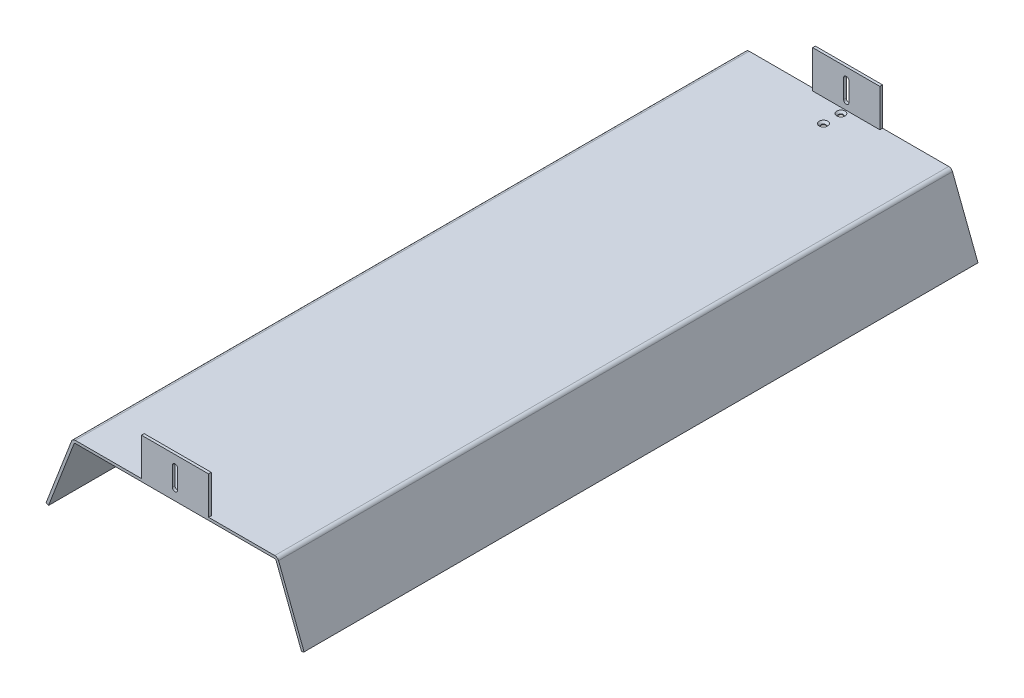
SolidWorks part; units mm, degrees
other "DetailItem1"
other "DetailItem2"
ref_plane "Front Plane" through (0, 0, 0) normal (0, 0, 1) x (1, 0, 0)
ref_plane "Top Plane" through (0, 0, 0) normal (0, 1, 0) x (1, 0, 0)
ref_plane "Right Plane" through (0, 0, 0) normal (1, 0, 0) x (0, 0, -1)
sketch "Sketch1" plane through (0, 0, 0) normal (0, 0, 1) x (1, 0, 0)
  line L0 (0, 113.4211) -> (0, -113.4211) construction
  line L1 (75, 0) -> (-75, 0)
  line L2 (-75, 0) -> (-94.25, -50)
  line L3 (75, 0) -> (94.25, -50)
  point P4 (0, 0)
  point P10 (0, 0)
  dimension "D1" = 150
  dimension "D2" = 188.5
  dimension "D3" = 50
extrude "Extrude-Thin1" add sketch "Sketch1" along normal blind 502 thin contours L1 L2
sketch "Sketch2" plane through (0, 0, 502) normal (0, 0, 1) x (1, 0, 0)
  line L0 (74.3134, 2) -> (-74.3134, 2) construction
  line L1 (-12.5, 2) -> (12.5, 2) construction
  line L2 (-12.5, 2) -> (-12.5, -18) construction
  line L3 (-12.5, -18) -> (12.5, -18) construction
  line L4 (12.5, 2) -> (12.5, -18) construction
  line L5 (0, 2) -> (0, -18) construction
  line L6 (-12.5, -8) -> (12.5, -8) construction
  line L7 (-2.5, -8) -> (2.5, -8) construction
  line L8 (-2.5, -5.5) -> (2.5, -5.5)
  line L9 (-2.5, -10.5) -> (2.5, -10.5)
  arc A0 (-2.5, -5.5) -> (-2.5, -10.5) centre (-2.5, -8) ccw
  arc A1 (2.5, -10.5) -> (2.5, -5.5) centre (2.5, -8) ccw
  point P6 (0, 2)
  point P14 (0, -8)
  dimension "D4" = 10
  dimension "D1" = 20
  dimension "D2" = 25
  dimension "D3" = 5
sketch "Sketch3" plane through (0, 0, 502) normal (0, 0, 1) x (1, 0, 0)
  line L0 (74.3134, 0) -> (-74.3134, 0) construction
  line L1 (-25, 0) -> (25, 0)
  line L2 (-25, 0) -> (-25, 30)
  line L3 (-25, 30) -> (25, 30)
  line L4 (25, 0) -> (25, 30)
  line L5 (0, 22) -> (0, 8) construction
  line L6 (2, 22) -> (2, 8)
  line L7 (-2, 22) -> (-2, 8)
  arc A0 (2, 22) -> (-2, 22) centre (0, 22) ccw
  arc A1 (-2, 8) -> (2, 8) centre (0, 8) ccw
  point P8 (0, 15)
  point P15 (0, 0)
  point P17 (-25, 15)
  dimension "D2" = 14
  dimension "D1" = 4
  dimension "D3" = 50
  dimension "D4" = 30
extrude "Boss-Extrude1" add sketch "Sketch3" against normal blind 2
ref_plane "Plane1" through (0, 0, 251) normal (0, 0, 1) x (1, 0, 0)
mirror "Mirror1" about plane through (0, 0, 251) normal (0, 0, 1) of bodies 102
sketch "Sketch4" plane through (0, 2, 0) normal (0, 1, 0) x (1, 0, 0)
  line L0 (0, -6) -> (0, -19) construction
  line L1 (-25, 0) -> (25, 0) construction
  line L2 (-25, 0) -> (-25, -25) construction
  line L3 (-25, -25) -> (25, -25) construction
  line L4 (25, 0) -> (25, -25) construction
  line L5 (2, -6) -> (2, -19) construction
  line L6 (-2, -6) -> (-2, -19) construction
  line L7 (25, -2) -> (25, 0) construction
  arc A0 (2, -6) -> (-2, -6) centre (0, -6) ccw construction
  arc A1 (-2, -19) -> (2, -19) centre (0, -19) ccw construction
  point P10 (0, -12.5)
  point P16 (-25, -12.5)
  point P18 (0, -6)
  point P20 (0, -19)
  dimension "D3" = 13
  dimension "D1" = 25
  dimension "D2" = 4
hole_wizard "CSK for M3 Countersunk Flat Head Screw1" positions "Sketch4" profile "Sketch5" countersink size "M3" standard "DIN"
sketch "Sketch5" plane through (0, 2, 19) normal (1, 0, 0) x (0, 0, 1)
  line L0 (0, 0) -> (0, 26.0215)
  line L1 (0, 26.0215) -> (1.7, 25)
  line L2 (1.7, 25) -> (1.7, 1.45)
  line L3 (1.7, 1.45) -> (3.15, 0)
  line L5 (3.15, 0) -> (0, 0)
  line L6 (-1.7, 1.45) -> (-3.15, 0) construction
  line L10 (0, 26.0215) -> (-1.7, 25) construction
  line L11 (0, -6.35) -> (0, 107.95) construction
  dimension "Hole Dia." = 3.4
  dimension "Hole Depth" = 25
  dimension "Near C'Sink Dia." = 6.3
  dimension "Near C'Sink Angle" = 90
  dimension "Drill Angle" = 118
mirror "Mirror2" about plane through (0, 0, 251) normal (0, 0, 1) of "CSK for M3 Countersunk Flat Head Screw1"
sketch "Sketch6" plane through (0, 0, 0) normal (0, 0, -1) x (-1, 0, 0)
  line L0 (-96.1165, -49.2814) -> (-77.1131, 0.0779) construction
  line L1 (-88.3081, -29) -> (-68.1156, -29)
  line L3 (-87.9231, -28) -> (-68.1156, -28)
  line L4 (-68.1156, -29) -> (-68.1156, -28)
  line L5 (-88.3081, -29) -> (-87.9231, -28)
  line L6 (12.5, -18) -> (-12.5, -18) construction
  point P2 (-88.1156, -28.5)
  dimension "D1" = 10
  dimension "D2" = 1
  dimension "D3" = 20
